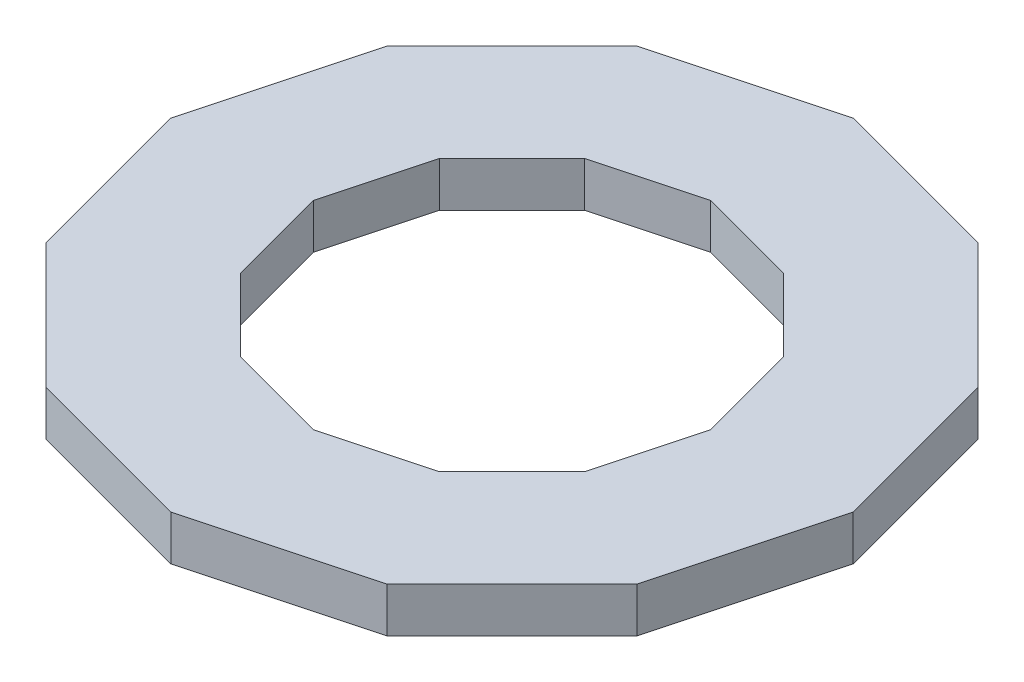
SolidWorks part; units mm, degrees
ref_plane "Front Plane" through (0, 0, 0) normal (0, 0, 1) x (1, 0, 0)
ref_plane "Top Plane" through (0, 0, 0) normal (0, 1, 0) x (1, 0, 0)
ref_plane "Right Plane" through (0, 0, 0) normal (1, 0, 0) x (0, 0, -1)
sketch "Sketch1" plane through (0, 0, 0) normal (0, 1, 0) x (1, 0, 0)
  line L1 (84.9461, 0) -> (78.4799, 32.5075)
  line L2 (78.4799, 32.5075) -> (60.0659, 60.0659)
  line L3 (60.0659, 60.0659) -> (32.5075, 78.4799)
  line L4 (32.5075, 78.4799) -> (0, 84.9461)
  line L5 (0, 84.9461) -> (-32.5075, 78.4799)
  line L6 (-32.5075, 78.4799) -> (-60.0659, 60.0659)
  line L7 (-60.0659, 60.0659) -> (-78.4799, 32.5075)
  line L8 (-78.4799, 32.5075) -> (-84.9461, 0)
  line L9 (-84.9461, 0) -> (-78.4799, -32.5075)
  line L10 (-78.4799, -32.5075) -> (-60.0659, -60.0659)
  line L11 (-60.0659, -60.0659) -> (-32.5075, -78.4799)
  line L12 (-32.5075, -78.4799) -> (0, -84.9461)
  line L13 (0, -84.9461) -> (32.5075, -78.4799)
  line L14 (32.5075, -78.4799) -> (60.0659, -60.0659)
  line L15 (60.0659, -60.0659) -> (78.4799, -32.5075)
  line L16 (78.4799, -32.5075) -> (84.9461, 0)
  line L17 (143.2157, 0) -> (132.3141, 54.8063)
  line L18 (132.3141, 54.8063) -> (101.2688, 101.2688)
  line L19 (101.2688, 101.2688) -> (54.8063, 132.3141)
  line L20 (54.8063, 132.3141) -> (0, 143.2157)
  line L21 (0, 143.2157) -> (-54.8063, 132.3141)
  line L22 (-54.8063, 132.3141) -> (-101.2688, 101.2688)
  line L23 (-101.2688, 101.2688) -> (-132.3141, 54.8063)
  line L24 (-132.3141, 54.8063) -> (-143.2157, 0)
  line L25 (-143.2157, 0) -> (-132.3141, -54.8063)
  line L26 (-132.3141, -54.8063) -> (-101.2688, -101.2688)
  line L27 (-101.2688, -101.2688) -> (-54.8063, -132.3141)
  line L28 (-54.8063, -132.3141) -> (0, -143.2157)
  line L29 (0, -143.2157) -> (54.8063, -132.3141)
  line L30 (54.8063, -132.3141) -> (101.2688, -101.2688)
  line L31 (101.2688, -101.2688) -> (132.3141, -54.8063)
  line L32 (132.3141, -54.8063) -> (143.2157, 0)
  circle A1 centre (0, 0) radius 83.3139 construction
  circle A2 centre (0, 0) radius 140.4639 construction
  dimension "D1" = 57.15
  dimension "D2" = 55.88
sketch "Sketch2" plane through (0, 0, 0) normal (0, 1, 0) x (1, 0, 0)
  line L0 (0, 0) -> (-84.2728, 0) construction
  line L1 (-144.7536, 0) -> (-125.3603, -72.3768)
  line L2 (-125.3603, -72.3768) -> (-72.3768, -125.3603)
  line L3 (-72.3768, -125.3603) -> (0, -144.7536)
  line L4 (0, -144.7536) -> (72.3768, -125.3603)
  line L5 (72.3768, -125.3603) -> (125.3603, -72.3768)
  line L6 (125.3603, -72.3768) -> (144.7536, 0)
  line L7 (144.7536, 0) -> (125.3603, 72.3768)
  line L8 (125.3603, 72.3768) -> (72.3768, 125.3603)
  line L9 (72.3768, 125.3603) -> (0, 144.7536)
  line L10 (0, 144.7536) -> (-72.3768, 125.3603)
  line L11 (-72.3768, 125.3603) -> (-125.3603, 72.3768)
  line L12 (-125.3603, 72.3768) -> (-144.7536, 0)
  line L13 (-84.2728, 0) -> (-72.9824, -42.1364)
  line L14 (-72.9824, -42.1364) -> (-42.1364, -72.9824)
  line L15 (-42.1364, -72.9824) -> (0, -84.2728)
  line L16 (0, -84.2728) -> (42.1364, -72.9824)
  line L17 (42.1364, -72.9824) -> (72.9824, -42.1364)
  line L18 (72.9824, -42.1364) -> (84.2728, 0)
  line L19 (84.2728, 0) -> (72.9824, 42.1364)
  line L20 (72.9824, 42.1364) -> (42.1364, 72.9824)
  line L21 (42.1364, 72.9824) -> (0, 84.2728)
  line L22 (0, 84.2728) -> (-42.1364, 72.9824)
  line L23 (-42.1364, 72.9824) -> (-72.9824, 42.1364)
  line L24 (-72.9824, 42.1364) -> (-84.2728, 0)
  line L25 (-144.7536, 0) -> (-84.2728, 0) construction
  circle A0 centre (0, 0) radius 139.8213 construction
  circle A1 centre (0, 0) radius 81.4013 construction
  dimension "D1" = 74.93
  dimension "D2" = 58.42
extrude "Boss-Extrude2" add sketch "Sketch2" along normal blind 19.05 separate body
